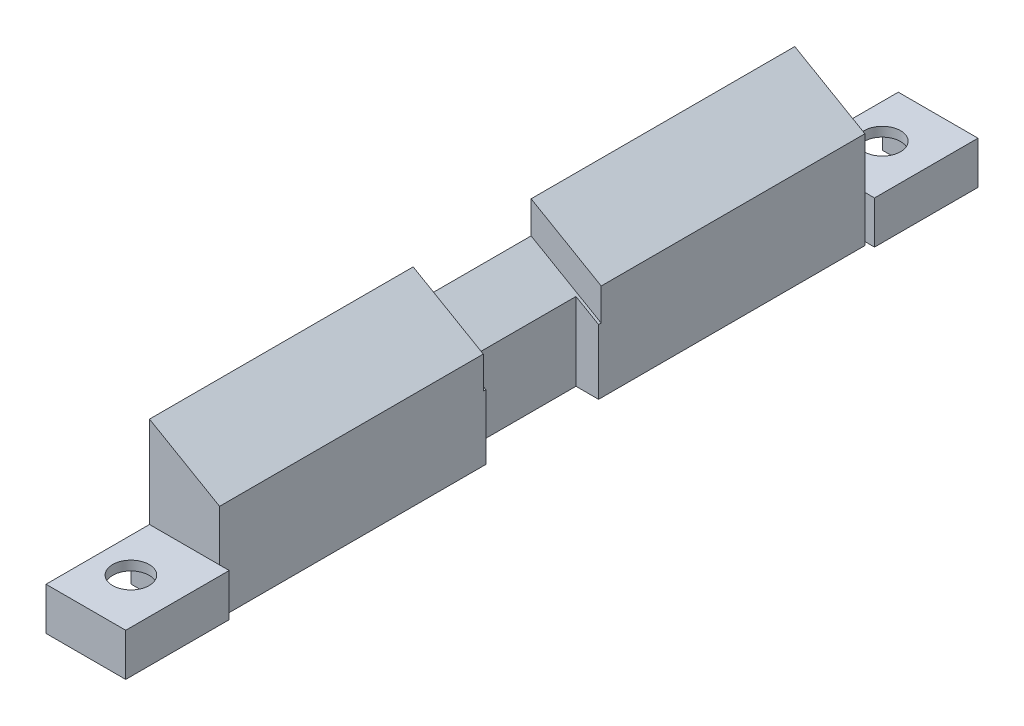
SolidWorks part; units mm, degrees
ref_plane "Front Plane" through (0, 0, 0) normal (0, 0, 1) x (1, 0, 0)
ref_plane "Top Plane" through (0, 0, 0) normal (0, 1, 0) x (1, 0, 0)
ref_plane "Right Plane" through (0, 0, 0) normal (1, 0, 0) x (0, 0, -1)
other "Configuration Table"
sketch "Sketch1" plane through (0, 0, 0) normal (0, 0, 1) x (1, 0, 0)
  line L0 (13.3671, 18.6) -> (17.3973, 18.6)
  line L1 (17.3973, 18.6) -> (17.3973, 24.1701)
  line L2 (17.3973, 24.1701) -> (13.3671, 26.4969)
  line L3 (13.3671, 26.4969) -> (13.3671, 18.6)
extrude "Clamp +X cover" add sketch "Sketch1" along normal blind 37.1 from offset 20.15
sketch "Sketch2" plane through (0, 0, 0) normal (0, 0, 1) x (1, 0, 0)
  line L0 (11.1021, 27.9201) -> (19.7623, 22.9201)
  line L1 (19.7623, 22.9201) -> (18.9123, 21.4479)
  line L2 (18.9123, 21.4479) -> (10.2521, 26.4479)
  line L3 (10.2521, 26.4479) -> (11.1021, 27.9201)
extrude "Wire channel +X cover Z -5.0" cut sketch "Sketch2" along normal blind 6.78 from offset 4.99
sketch "Sketch3" plane through (0, 0, 0) normal (0, 0, 1) x (1, 0, 0)
  line L0 (16.0973, 18.5) -> (17.6973, 18.5)
  line L1 (17.6973, 18.5) -> (17.6973, 23.9207)
  line L2 (17.6973, 23.9207) -> (16.0973, 23.9207)
  line L3 (16.0973, 23.9207) -> (16.0973, 18.5)
extrude "Wire notch +X cover Z -5.0" cut sketch "Sketch3" along normal blind 6.48 from offset 4.84
sketch "Sketch4" plane through (0, 0, 0) normal (0, 0, 1) x (1, 0, 0)
  line L0 (13.3671, 18.8) -> (17.95, 18.8)
  line L1 (17.95, 18.8) -> (17.95, 21.25)
  line L2 (17.95, 21.25) -> (13.3671, 21.25)
  line L3 (13.3671, 21.25) -> (13.3671, 18.8)
extrude "Ear +X cover -26" add sketch "Sketch4" along normal blind 5.95 from offset 26.1
sketch "Sketch5" plane through (0, 0, 0) normal (0, 0, 1) x (1, 0, 0)
  line L0 (13.3671, 18.8) -> (17.95, 18.8)
  line L1 (17.95, 18.8) -> (17.95, 21.25)
  line L2 (17.95, 21.25) -> (13.3671, 21.25)
  line L3 (13.3671, 21.25) -> (13.3671, 18.8)
extrude "Ear +X cover 17" add sketch "Sketch5" along normal blind 5.95 from offset 16.95
sketch "Sketch6" plane through (0, 0, 0) normal (0, 1, 0) x (1, 0, 0)
  circle A0 centre (15.35, 23.2) radius 1.05
  circle A1 centre (15.35, -20) radius 1.05
extrude "Cut-Extrude3" cut sketch "Sketch6" along normal blind 2.65 from offset 18.7
sketch "Sketch7" plane through (0, 0, 0) normal (0, 1, 0) x (1, 0, 0)
  circle A0 centre (15.35, 23.2) radius 2
  circle A1 centre (15.35, -20) radius 2
extrude "Cut-Extrude4" cut sketch "Sketch7" along normal blind 1.92 from offset 18.79
sketch "Sketch8" plane through (0, 0, 0) normal (0, 1, 0) x (1, 0, 0)
  line L1 (13.2671, 25.2) -> (15.35, 25.2)
  line L2 (13.2671, 25.2) -> (13.2671, 21.2)
  line L3 (13.2671, 21.2) -> (15.35, 21.2)
  line L4 (15.35, 25.2) -> (15.35, 21.2)
  line L6 (13.2671, -18) -> (15.35, -18)
  line L7 (13.2671, -18) -> (13.2671, -22)
  line L8 (13.2671, -22) -> (15.35, -22)
  line L9 (15.35, -18) -> (15.35, -22)
extrude "Cut-Extrude5" cut sketch "Sketch8" along normal blind 1.92 from offset 18.79
sketch "Sketch9" plane through (0, 0, 0) normal (0, 1, 0) x (1, 0, 0)
  line L0 (15.35, 25.2) -> (16.7642, 24.6142)
  line L1 (16.7642, 24.6142) -> (17.35, 24.0284)
  line L2 (17.35, 24.0284) -> (17.35, 22.3716)
  line L3 (17.35, 22.3716) -> (16.7642, 21.7858)
  line L4 (16.7642, 21.7858) -> (15.35, 21.2)
  line L5 (15.35, 21.2) -> (15.35, 25.2)
extrude "Cut-Extrude6" cut sketch "Sketch9" along normal blind 1.92 from offset 18.79
sketch "Sketch10" plane through (0, 0, 0) normal (0, 1, 0) x (1, 0, 0)
  line L0 (15.35, -18) -> (16.7642, -18.5858)
  line L1 (16.7642, -18.5858) -> (17.35, -19.1716)
  line L2 (17.35, -19.1716) -> (17.35, -20.8284)
  line L3 (17.35, -20.8284) -> (16.7642, -21.4142)
  line L4 (16.7642, -21.4142) -> (15.35, -22)
  line L5 (15.35, -22) -> (15.35, -18)
extrude "Cut-Extrude7" cut sketch "Sketch10" along normal blind 1.92 from offset 18.79
